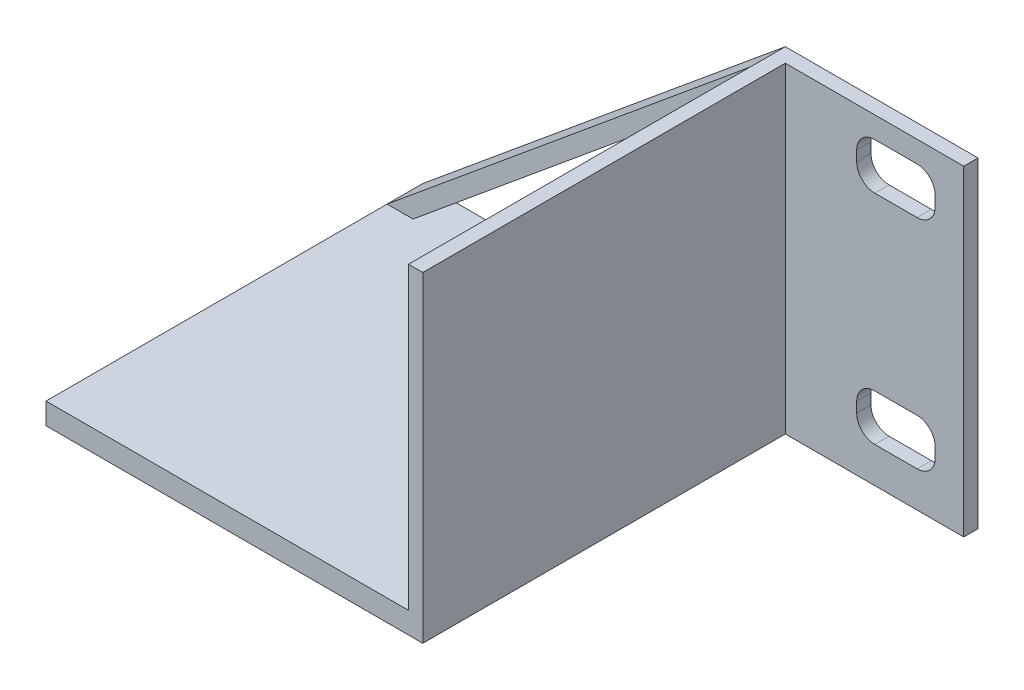
SolidWorks part; units mm, degrees
ref_plane "Front Plane" through (0, 0, 0) normal (0, 0, 1) x (1, 0, 0)
ref_plane "Top Plane" through (0, 0, 0) normal (0, 1, 0) x (1, 0, 0)
ref_plane "Right Plane" through (0, 0, 0) normal (1, 0, 0) x (0, 0, -1)
sketch "Sketch1" plane through (0, 0, 0) normal (0, 0, 1) x (1, 0, 0)
  line L1 (0, 0) -> (-25, 0)
  line L2 (0, 0) -> (0, 45)
  line L3 (0, 45) -> (-25, 45)
  line L4 (-25, 0) -> (-25, 45)
  dimension "D1" = 25
  dimension "D2" = 45
extrude "Boss-Extrude1" add sketch "Sketch1" along normal blind 2
sketch "Sketch2" plane through (0, 0, 2) normal (0, 0, 1) x (1, 0, 0)
  line L2 (-15, 11.5) -> (-15, 5)
  line L4 (-15, 5) -> (-4, 5)
  line L6 (-15, 35.5) -> (-4, 35.5)
  line L7 (-15, 42) -> (-15, 35.5)
  line L8 (-4, 35.5) -> (-4, 42)
  line L9 (-4, 42) -> (-15, 42)
  line L10 (-4, 5) -> (-4, 11.5)
  line L11 (-4, 11.5) -> (-15, 11.5)
  dimension "D1" = 24
  dimension "D2" = 6.5
  dimension "D3" = 11
  dimension "D4" = 11
extrude "Cut-Extrude1" cut sketch "Sketch2" against normal blind 19.78
fillet "Fillet1" radius 2.54 8 edges at (-15, 5, 1) (-15, 11.5, 1) (-4, 5, 1) (-4, 11.5, 1) (-4, 35.5, 1) (-4, 42, 1) (-15, 42, 1) (-15, 35.5, 1)
sketch "Sketch9" plane through (-25, 0, 0) normal (-1, 0, 0) x (0, 0, 1)
  line L1 (0, 45) -> (2, 45)
  line L2 (0, 45) -> (0, 0)
  line L3 (0, 0) -> (2, 0)
  line L5 (2, 45) -> (52.8, 45)
  line L7 (2, 0) -> (52.8, 0)
  line L8 (52.8, 45) -> (52.8, 0)
  dimension "D1" = 50.8
extrude "Boss-Extrude5" add sketch "Sketch9" along normal blind 2
sketch "Sketch10" plane through (-27, 0, 0) normal (-1, 0, 0) x (0, 0, 1)
  line L0 (52.8, 0) -> (52.8, 45) construction
  line L1 (0, 0) -> (52.8, 0)
  line L2 (0, 0) -> (0, 3)
  line L3 (0, 3) -> (52.8, 3)
  line L4 (52.8, 0) -> (52.8, 3)
  dimension "D1" = 3
extrude "Boss-Extrude6" add sketch "Sketch10" along normal blind 50.8
sketch "Sketch11" plane through (0, 0, 0) normal (0, 0, -1) x (-1, 0, 0)
  line L0 (27, 45) -> (77.8, 3)
  line L1 (77.8, 3) -> (77.8, 0)
  line L2 (77.8, 0) -> (27, 42)
  line L3 (27, 45) -> (27, 3) construction
  line L4 (27, 42) -> (27, 45)
extrude "Boss-Extrude7" add sketch "Sketch11" against normal blind 5
sketch "Sketch12" plane through (0, 3, 0) normal (0, 1, 0) x (1, 0, 0)
  circle A0 centre (-39.7, -17.7) radius 6.35
  dimension "D2" = 12.7
extrude "Cut-Extrude4" cut sketch "Sketch12" against normal blind 5
